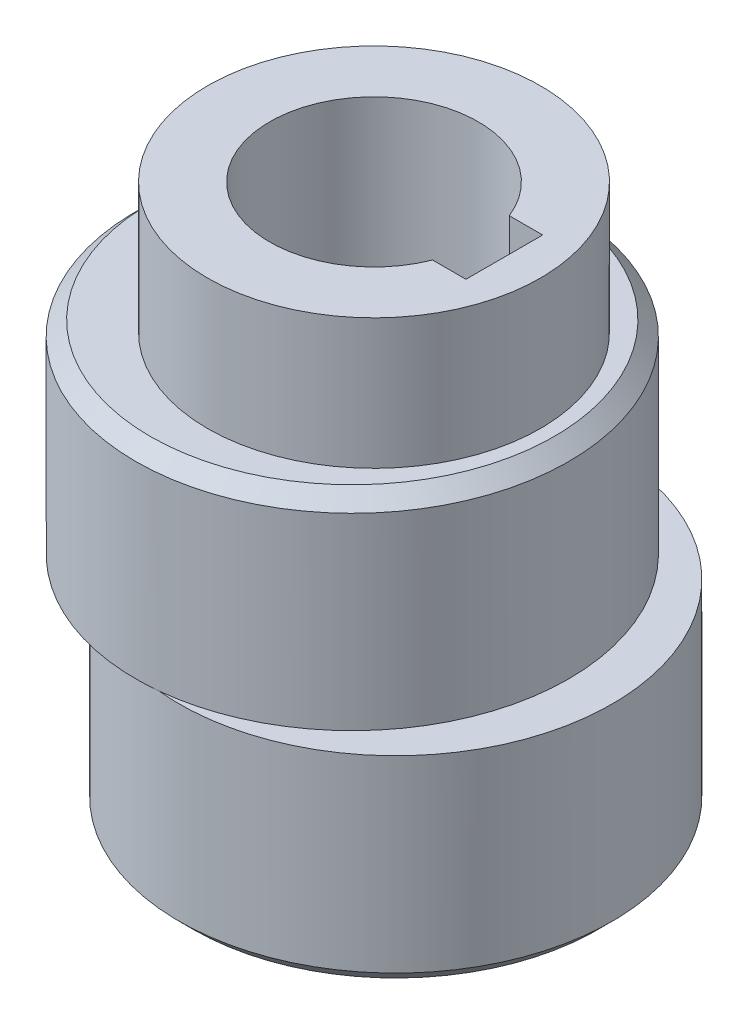
SolidWorks part; units mm, degrees
ref_plane "Front Plane" through (0, 0, 0) normal (0, 0, 1) x (1, 0, 0)
ref_plane "Top Plane" through (0, 0, 0) normal (0, 1, 0) x (1, 0, 0)
ref_plane "Right Plane" through (0, 0, 0) normal (1, 0, 0) x (0, 0, -1)
sketch "Sketch1" plane through (0, 0, 0) normal (0, 1, 0) x (1, 0, 0)
  circle A0 centre (0, 0) radius 14.95
  dimension "D1" = 29.9
extrude "Boss-Extrude1" add sketch "Sketch1" along normal blind 14
sketch "Sketch3" plane through (0, 0, 0) normal (0, -1, 0) x (1, 0, 0)
  line L0 (0, 0) -> (3, 0) construction
  circle A0 centre (3, 0) radius 14.95
  point P0 (3, -0.2602)
  dimension "D1" = 29.9
  dimension "D2" = 3
extrude "Boss-Extrude2" add sketch "Sketch3" along normal blind 14
sketch "Sketch4" plane through (0, -14, 0) normal (0, -1, 0) x (1, 0, 0)
  line L0 (0, 0) -> (1.5, 0) construction
  circle A0 centre (1.5, 0) radius 7.2
  dimension "D2" = 14.4
  dimension "D1" = 1.5
chamfer "Chamfer1" distance 1 angle 45 2 edges at (3, -14, -14.95) (0, 14, 14.95)
sketch "Sketch6" plane through (0, 14, 0) normal (0, 1, 0) x (1, 0, 0)
  line L0 (1.5, 0) -> (11.4363, 0) construction
  line L1 (7.7818, 2.65) -> (10.5, 2.65)
  line L2 (10.5, 2.65) -> (10.5, -2.65)
  line L3 (10.5, -2.65) -> (7.7818, -2.65)
  line L4 (7.7818, -2.65) -> (7.7818, 2.65)
  line L5 (1.5, 0) -> (-5.7, 0) construction
  circle A1 centre (1.5, 0) radius 7.2 construction
  dimension "D1" = 5.3
  dimension "D2" = 16.2
sketch "Sketch9" plane through (0, 14, 0) normal (0, 1, 0) x (1, 0, 0)
  line L0 (1.5, 0) -> (11.4363, 0) construction
  circle A0 centre (1.5, 0) radius 7.2
  point P3 (1, 0)
  point P4 (1.9862, 0)
  dimension "D1" = 1.5
sketch "Sketch10" plane through (0, 14, 0) normal (0, 1, 0) x (1, 0, 0)
  line L0 (7.7818, -2.65) -> (7.7818, 2.65) construction
  line L1 (7.7818, 2.65) -> (10.5, 2.65) construction
  line L2 (10.5, 2.65) -> (10.5, -2.65) construction
  line L3 (10.5, -2.65) -> (7.7818, -2.65) construction
  line L4 (7.7818, -2.65) -> (7.7818, 2.65)
  line L5 (7.7818, 2.65) -> (10.5, 2.65)
  line L6 (10.5, 2.65) -> (10.5, -2.65)
  line L7 (10.5, -2.65) -> (7.7818, -2.65)
sketch "Sketch11" plane through (0, 14, 0) normal (0, 1, 0) x (1, 0, 0)
  circle A0 centre (1.5, 0) radius 11.5
  dimension "D1" = 23
extrude "Boss-Extrude3" add sketch "Sketch11" along normal blind 9
extrude "Cut-Extrude1" cut sketch "Sketch9" against normal through all and the other way through all
extrude "Cut-Extrude2" cut sketch "Sketch10" against normal through all and the other way through all
